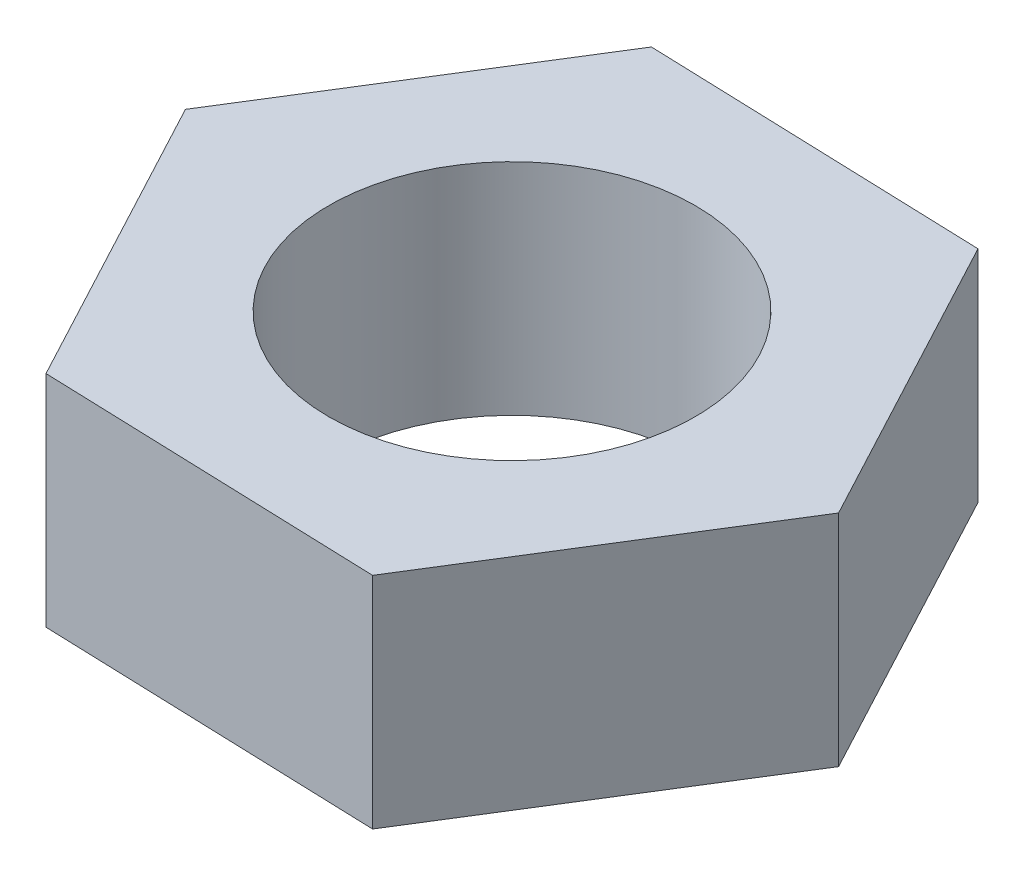
SolidWorks part; units mm, degrees
ref_plane "前视基准面" through (0, 0, 0) normal (0, 0, 1) x (1, 0, 0)
ref_plane "上视基准面" through (0, 0, 0) normal (0, 1, 0) x (1, 0, 0)
ref_plane "右视基准面" through (0, 0, 0) normal (1, 0, 0) x (0, 0, -1)
sketch "草图1" plane through (0, 0, 0) normal (0, 1, 0) x (1, 0, 0)
  line L1 (2.4439, 3.9193) -> (-2.1722, 4.0761)
  line L2 (-2.1722, 4.0761) -> (-4.6161, 0.1568)
  line L3 (-4.6161, 0.1568) -> (-2.4439, -3.9193)
  line L4 (-2.4439, -3.9193) -> (2.1722, -4.0761)
  line L5 (2.1722, -4.0761) -> (4.6161, -0.1568)
  line L6 (4.6161, -0.1568) -> (2.4439, 3.9193)
  circle A1 centre (0, 0) radius 4 construction
  dimension "D1" = 8
extrude "凸台-拉伸1" add sketch "草图1" along normal blind 3 contours L6 L1 L2 L3 L4 L5
sketch "草图2" plane through (0, 3, 0) normal (0, 1, 0) x (1, 0, 0)
  line L0 (2.4439, 3.9193) -> (-2.1722, 4.0761) construction
  circle A0 centre (0, 0) radius 4
extrude "凸台-拉伸2" add sketch "草图2" along normal blind 1
sketch "草图4" plane through (0, 4, 0) normal (0, 1, 0) x (1, 0, 0)
  circle A0 centre (0, 0) radius 2.5
  dimension "D1" = 5
extrude "切除-拉伸1" cut sketch "草图4" against normal through all
cosmetic thread "装饰螺纹线1" parameters "D2"=6
sketch "草图5" plane through (0, 3, 0) normal (0, 1, 0) x (1, 0, 0)
  line L6 (2.1722, -4.0761) -> (4.6161, -0.1568)
  line L7 (-2.4439, -3.9193) -> (2.1722, -4.0761)
  line L8 (-4.6161, 0.1568) -> (-2.4439, -3.9193)
  line L9 (-2.1722, 4.0761) -> (-4.6161, 0.1568)
  line L10 (2.4439, 3.9193) -> (-2.1722, 4.0761)
  line L11 (4.6161, -0.1568) -> (2.4439, 3.9193)
  line L12 (2.1722, -4.0761) -> (4.6161, -0.1568)
  line L13 (-2.4439, -3.9193) -> (2.1722, -4.0761)
  line L14 (-4.6161, 0.1568) -> (-2.4439, -3.9193)
  line L15 (-2.1722, 4.0761) -> (-4.6161, 0.1568)
  line L16 (2.4439, 3.9193) -> (-2.1722, 4.0761)
  line L17 (4.6161, -0.1568) -> (2.4439, 3.9193)
  dimension "D1" = 0
extrude "切除-拉伸2" cut sketch "草图5" along normal blind 10
